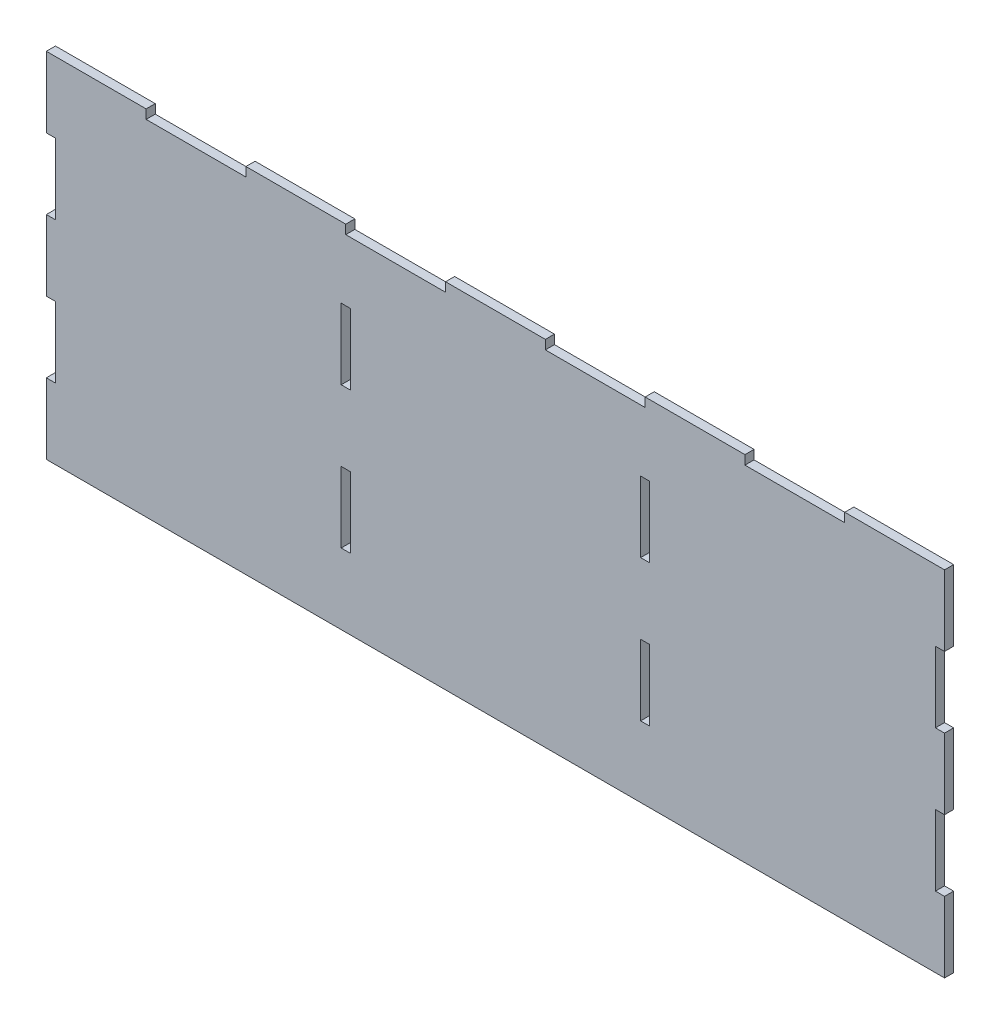
SolidWorks part; units mm, degrees
ref_plane "Front Plane" through (0, 0, 0) normal (0, 0, 1) x (1, 0, 0)
ref_plane "Top Plane" through (0, 0, 0) normal (0, 1, 0) x (1, 0, 0)
ref_plane "Right Plane" through (0, 0, 0) normal (1, 0, 0) x (0, 0, -1)
sketch "Sketch1" plane through (0, 0, 0) normal (0, 0, 1) x (1, 0, 0)
  line L0 (0, 120) -> (313, 120) construction
  line L1 (0, 0) -> (313, 0)
  line L2 (0, 0) -> (0, 123.175) construction
  line L4 (313, 0) -> (313, 123.175) construction
  line L22 (0, 123.175) -> (34.7778, 123.175)
  line L23 (34.7778, 123.175) -> (34.7778, 120)
  line L24 (34.7778, 120) -> (69.5556, 120)
  line L25 (69.5556, 120) -> (69.5556, 123.175)
  line L26 (69.5556, 123.175) -> (104.3333, 123.175)
  line L27 (104.3333, 123.175) -> (104.3333, 120)
  line L28 (104.3333, 120) -> (139.1111, 120)
  line L29 (139.1111, 120) -> (139.1111, 123.175)
  line L30 (139.1111, 123.175) -> (173.8889, 123.175)
  line L31 (173.8889, 123.175) -> (173.8889, 120)
  line L32 (173.8889, 120) -> (208.6667, 120)
  line L33 (208.6667, 120) -> (208.6667, 123.175)
  line L34 (208.6667, 123.175) -> (243.4444, 123.175)
  line L35 (243.4444, 123.175) -> (243.4444, 120)
  line L36 (243.4444, 120) -> (278.2222, 120)
  line L37 (278.2222, 120) -> (278.2222, 123.175)
  line L38 (278.2222, 123.175) -> (313, 123.175)
  line L39 (0, 123.175) -> (0, 98.54)
  line L44 (0, 98.54) -> (3.175, 98.54)
  line L45 (3.175, 98.54) -> (3.175, 73.905)
  line L46 (3.175, 73.905) -> (0, 73.905)
  line L47 (0, 73.905) -> (0, 49.27)
  line L48 (0, 49.27) -> (3.175, 49.27)
  line L49 (3.175, 49.27) -> (3.175, 24.635)
  line L50 (3.175, 24.635) -> (0, 24.635)
  line L51 (0, 24.635) -> (0, 0)
  line L52 (104.3333, 120) -> (104.3333, 0) construction
  line L53 (208.6667, 120) -> (208.6667, 0) construction
  line L54 (313, 123.175) -> (313, 98.54)
  line L55 (313, 98.54) -> (309.825, 98.54)
  line L56 (309.825, 98.54) -> (309.825, 73.905)
  line L57 (309.825, 73.905) -> (313, 73.905)
  line L58 (313, 73.905) -> (313, 49.27)
  line L59 (313, 49.27) -> (309.825, 49.27)
  line L60 (309.825, 49.27) -> (309.825, 24.635)
  line L61 (309.825, 24.635) -> (313, 24.635)
  line L62 (313, 24.635) -> (313, 0)
  line L63 (3.175, 98.54) -> (309.825, 98.54) construction
  line L64 (309.825, 73.905) -> (3.175, 73.905) construction
  line L65 (3.175, 49.27) -> (309.825, 49.27) construction
  line L66 (309.825, 24.635) -> (3.175, 24.635) construction
  line L68 (105.9208, 98.54) -> (102.7458, 98.54)
  line L69 (105.9208, 98.54) -> (105.9208, 73.905)
  line L70 (105.9208, 73.905) -> (102.7458, 73.905)
  line L71 (102.7458, 98.54) -> (102.7458, 73.905)
  line L72 (105.9208, 49.27) -> (102.7458, 49.27)
  line L73 (105.9208, 49.27) -> (105.9208, 24.635)
  line L74 (105.9208, 24.635) -> (102.7458, 24.635)
  line L75 (102.7458, 49.27) -> (102.7458, 24.635)
  line L76 (210.2542, 98.54) -> (207.0792, 98.54)
  line L77 (210.2542, 98.54) -> (210.2542, 73.905)
  line L78 (210.2542, 73.905) -> (207.0792, 73.905)
  line L79 (207.0792, 98.54) -> (207.0792, 73.905)
  line L80 (210.2542, 49.27) -> (207.0792, 49.27)
  line L81 (210.2542, 49.27) -> (210.2542, 24.635)
  line L82 (210.2542, 24.635) -> (207.0792, 24.635)
  line L83 (207.0792, 49.27) -> (207.0792, 24.635)
  point P45 (104.3333, 98.54)
  point P54 (208.6667, 98.54)
  dimension "D4" = 3.175
  dimension "D1" = 313
  dimension "D2" = 3.175
  dimension "D3" = 120
  dimension "D5" = 3.175
  dimension "D6" = 3.175
  dimension "D7" = 3.175
extrude "Boss-Extrude1" add sketch "Sketch1" along normal blind 3.175
